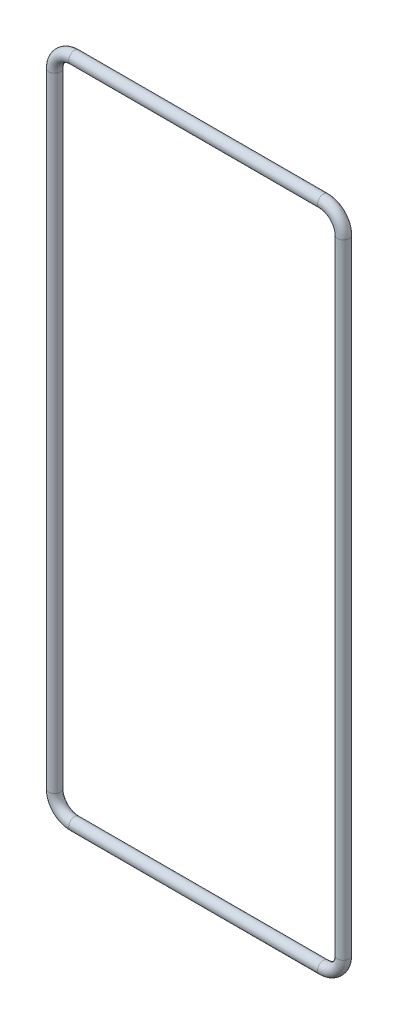
SolidWorks part; units mm, degrees
material "VITON"
ref_plane "Plano frontal" through (0, 0, 0) normal (0, 0, 1) x (1, 0, 0)
ref_plane "Plano superior" through (0, 0, 0) normal (0, 1, 0) x (1, 0, 0)
ref_plane "Plano direito" through (0, 0, 0) normal (1, 0, 0) x (0, 0, -1)
sketch "Esboço1" plane through (0, 0, 0) normal (0, 0, 1) x (1, 0, 0)
  line L1 (-37.5, -100) -> (37.5, -100)
  line L2 (-43.5, -94) -> (-43.5, 94)
  line L3 (-37.5, 100) -> (37.5, 100)
  line L4 (43.5, -94) -> (43.5, 94)
  line L5 (-43.5, -100) -> (43.5, 100) construction
  line L6 (-43.5, 100) -> (43.5, -100) construction
  arc A0 (-43.5, -94) -> (-37.5, -100) centre (-37.5, -94) ccw
  arc A1 (37.5, -100) -> (43.5, -94) centre (37.5, -94) ccw
  arc A2 (43.5, 94) -> (37.5, 100) centre (37.5, 94) ccw
  arc A3 (-37.5, 100) -> (-43.5, 94) centre (-37.5, 94) ccw
  point P0 (0, 0)
  dimension "D3" = 6
  dimension "D1" = 87
  dimension "D2" = 200
sketch "Esboço2" plane through (0, 0, 0) normal (0, 1, 0) x (1, 0, 0)
  line L0 (37.5, 0) -> (43.5, 0) construction
  circle A0 centre (43.5, 0) radius 1.765
  dimension "D1" = 3.53
sweep "Varredura1" add profiles "Esboço2" path "Esboço1"
